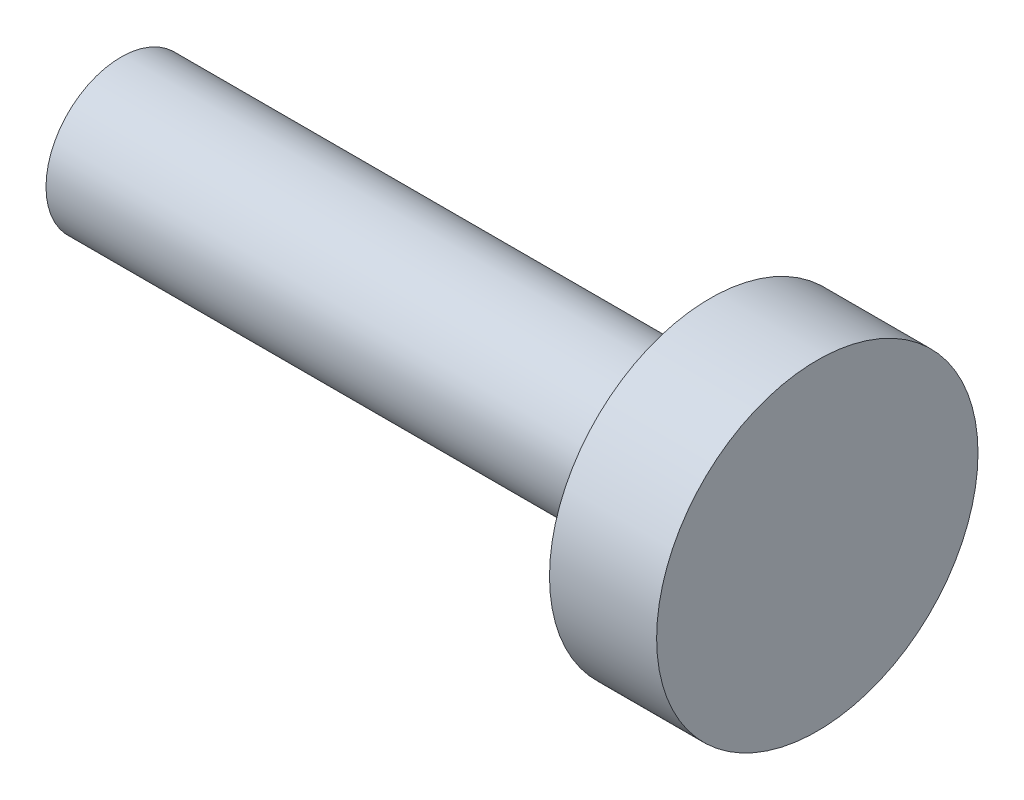
SolidWorks part; units mm, degrees
material "1023 Carbon Steel Sheet (SS)"
ref_plane "Front Plane" through (0, 0, 0) normal (0, 0, 1) x (1, 0, 0)
ref_plane "Top Plane" through (0, 0, 0) normal (0, 1, 0) x (1, 0, 0)
ref_plane "Right Plane" through (0, 0, 0) normal (1, 0, 0) x (0, 0, -1)
sketch "Sketch1" plane through (0, 0, 0) normal (0, 0, 1) x (1, 0, 0)
  line L0 (0, 0) -> (17.9294, 0) construction
  line L2 (3.4492, 0) -> (14.4492, 0)
  line L3 (3.4492, 0) -> (3.4492, 1.4)
  line L4 (3.4492, 1.4) -> (14.4492, 1.4)
  line L5 (14.4492, 0) -> (14.4492, 1.4)
  line L6 (14.4492, 0) -> (16.4492, 0)
  line L7 (14.4492, 0) -> (14.4492, 3)
  line L8 (14.4492, 3) -> (16.4492, 3)
  line L9 (16.4492, 0) -> (16.4492, 3)
  dimension "D1" = 11
  dimension "D2" = 1.4
  dimension "D3" = 2
  dimension "D4" = 3
revolve "Revolve1" add sketch "Sketch1" angle 360 about L0
